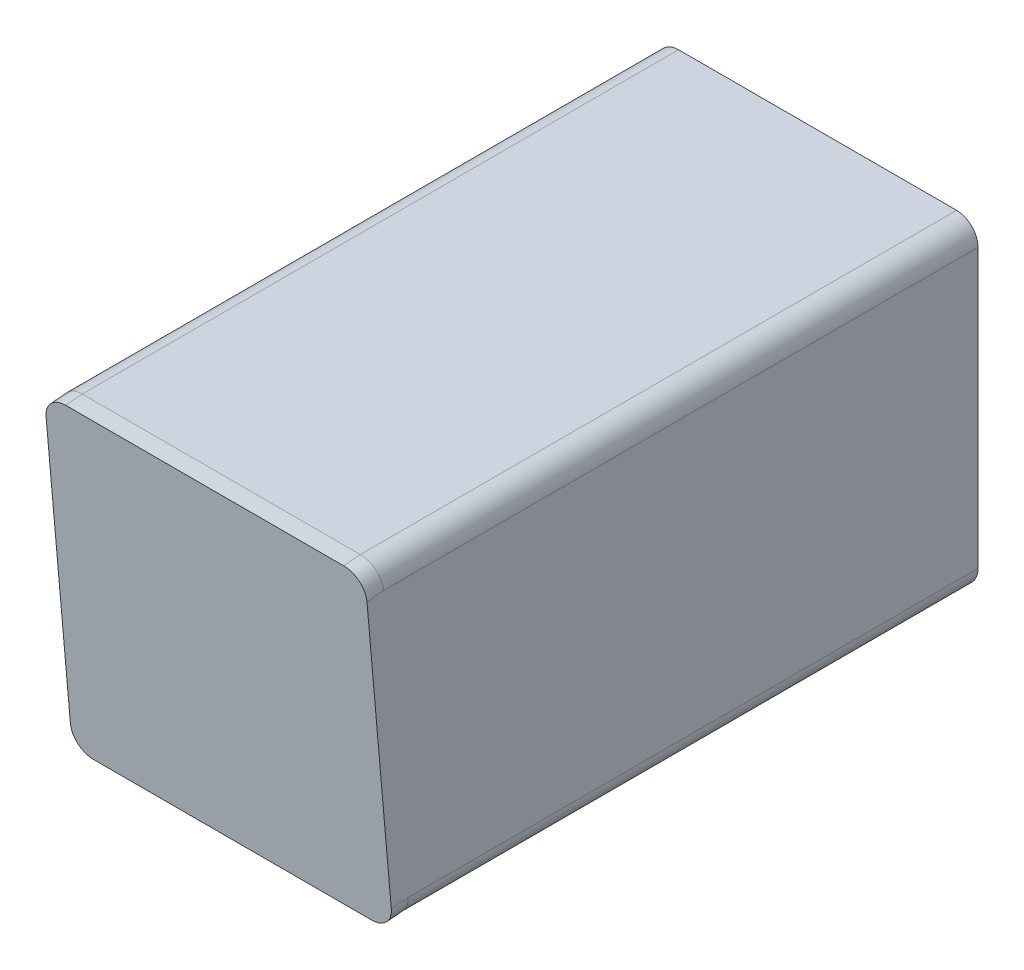
SolidWorks part; units mm, degrees
material "ASTM A500 Grade B Steel"
ref_plane "Front Plane" through (0, 0, 0) normal (0, 0, 1) x (1, 0, 0)
ref_plane "Top Plane" through (0, 0, 0) normal (0, 1, 0) x (1, 0, 0)
ref_plane "Right Plane" through (0, 0, 0) normal (1, 0, 0) x (0, 0, -1)
sketch "Sketch1" plane through (0, 0, 0) normal (0, 0, 1) x (1, 0, 0)
  line L0 (5.3086, -2.7686) -> (32.7914, -2.7686)
  line L1 (2.54, 0) -> (35.56, 0)
  line L2 (0, -2.54) -> (0, -35.56)
  line L3 (2.54, -38.1) -> (35.56, -38.1)
  line L4 (38.1, -2.54) -> (38.1, -35.56)
  line L5 (35.3314, -5.3086) -> (35.3314, -32.7914)
  line L6 (5.3086, -35.3314) -> (32.7914, -35.3314)
  line L7 (2.7686, -5.3086) -> (2.7686, -32.7914)
  line L8 (0, 0) -> (0, -38.1) construction
  line L9 (0, -38.1) -> (38.1, -38.1) construction
  line L10 (38.1, 0) -> (38.1, -38.1) construction
  line L11 (2.7686, -2.7686) -> (2.7686, -35.3314) construction
  line L12 (2.7686, -35.3314) -> (35.3314, -35.3314) construction
  line L13 (35.3314, -2.7686) -> (35.3314, -35.3314) construction
  line L14 (2.7686, -2.7686) -> (35.3314, -2.7686) construction
  line L15 (0, 0) -> (38.1, 0) construction
  arc A0 (0, -35.56) -> (2.54, -38.1) centre (2.54, -35.56) ccw
  arc A1 (38.1, -35.56) -> (35.56, -38.1) centre (35.56, -35.56) cw
  arc A2 (2.7686, -32.7914) -> (5.3086, -35.3314) centre (5.3086, -32.7914) ccw
  arc A3 (32.7914, -35.3314) -> (35.3314, -32.7914) centre (32.7914, -32.7914) ccw
  arc A4 (35.3314, -5.3086) -> (32.7914, -2.7686) centre (32.7914, -5.3086) ccw
  arc A5 (38.1, -2.54) -> (35.56, 0) centre (35.56, -2.54) ccw
  arc A6 (0, -2.54) -> (2.54, 0) centre (2.54, -2.54) cw
  arc A7 (5.3086, -2.7686) -> (2.7686, -5.3086) centre (5.3086, -5.3086) ccw
  point P12 (0, -38.1)
  dimension "D4" = 2.54
  dimension "D3" = 2.7686
extrude "Boss-Extrude1" add sketch "Sketch1" along normal blind 70.8
sketch "Sketch2" plane through (38.1, 0, 0) normal (1, 0, 0) x (0, 0, -1)
  line L0 (-70.8, 0) -> (-67.4667, -38.1)
  line L1 (-70.8, -38.1) -> (0, -38.1) construction
  line L2 (-67.4667, -38.1) -> (-70.8, -38.1)
  line L3 (-70.8, -38.1) -> (-70.8, 0)
  dimension "D1" = 5
extrude "Cut-Extrude1" cut sketch "Sketch2" against normal through all
sketch "Sketch3" plane through (0, -6.1471, 70.2622) normal (0, -0.0872, 0.9962) x (1, 0, 0)
  line L4 (2.54, -32.0749) -> (35.56, -32.0749)
  line L5 (38.1, -29.5252) -> (38.1, 3.6209)
  line L6 (35.56, 6.1706) -> (2.54, 6.1706)
  line L7 (0, 3.6209) -> (0, -29.5252)
  line L8 (2.54, -32.0749) -> (35.56, -32.0749)
  line L9 (38.1, -29.5252) -> (38.1, 3.6209)
  line L10 (35.56, 6.1706) -> (2.54, 6.1706)
  line L11 (0, 3.6209) -> (0, -29.5252)
  ellipse E4 centre (35.56, -29.5252) end of major axis (35.56, -32.0749) minor radius 2.54 (35.56, -32.0749) -> (38.1, -29.5252) ccw
  ellipse E5 centre (35.56, 3.6209) end of major axis (35.56, 1.0712) minor radius 2.54 (38.1, 3.6209) -> (35.56, 6.1706) ccw
  ellipse E6 centre (2.54, 3.6209) end of major axis (2.54, 1.0712) minor radius 2.54 (2.54, 6.1706) -> (0, 3.6209) ccw
  ellipse E7 centre (2.54, -29.5252) end of major axis (2.54, -32.0749) minor radius 2.54 (0, -29.5252) -> (2.54, -32.0749) ccw
  ellipse E8 centre (35.56, -29.5252) end of major axis (35.56, -32.0749) minor radius 2.54 (35.56, -32.0749) -> (38.1, -29.5252) ccw
  ellipse E9 centre (35.56, 3.6209) end of major axis (35.56, 1.0712) minor radius 2.54 (38.1, 3.6209) -> (35.56, 6.1706) ccw
  ellipse E10 centre (2.54, 3.6209) end of major axis (2.54, 1.0712) minor radius 2.54 (2.54, 6.1706) -> (0, 3.6209) ccw
  ellipse E11 centre (2.54, -29.5252) end of major axis (2.54, -32.0749) minor radius 2.54 (0, -29.5252) -> (2.54, -32.0749) ccw
  dimension "D1" = 0
extrude "Boss-Extrude2" add sketch "Sketch3" along normal up to surface (1.9765 mm away)
